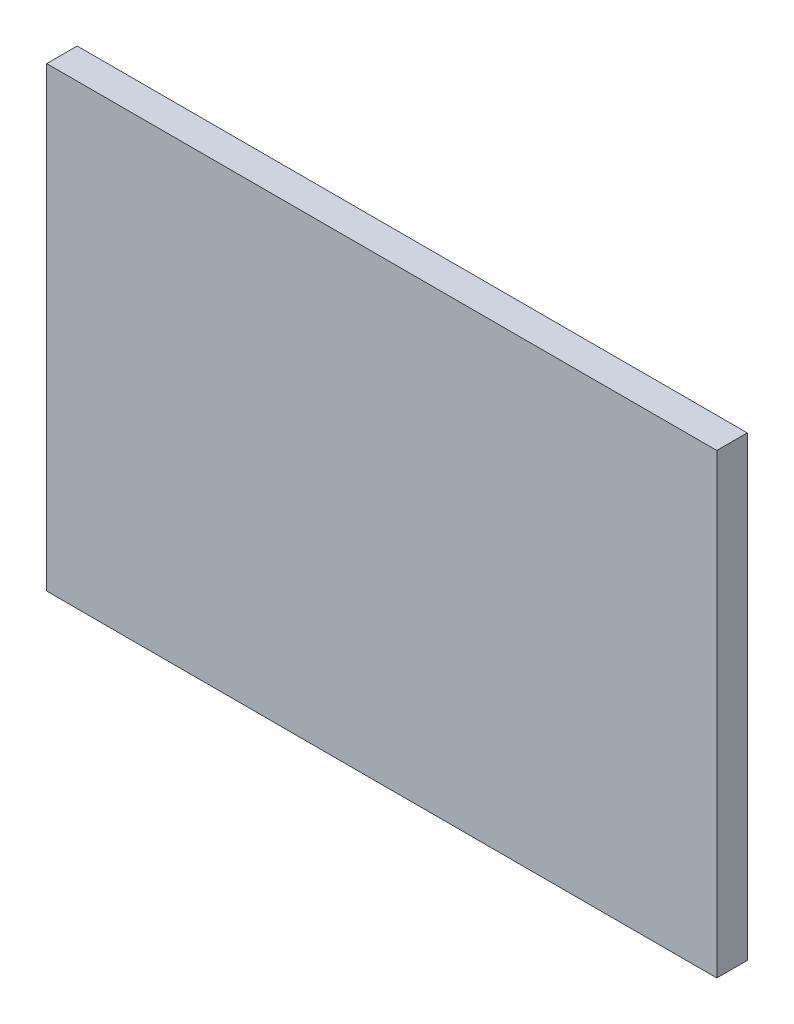
SolidWorks part; units mm, degrees
ref_plane "Alzado" through (0, 0, 0) normal (0, 0, 1) x (1, 0, 0)
ref_plane "Planta" through (0, 0, 0) normal (0, 1, 0) x (1, 0, 0)
ref_plane "Vista lateral" through (0, 0, 0) normal (1, 0, 0) x (0, 0, -1)
sketch "Croquis1" plane through (37728.547, 1888.5544, 0) normal (0, 0, 1) x (1, 0, 0)
  line L1 (-22281.5534, 13980.5825) -> (-281.5534, 13980.5825)
  line L2 (-22281.5534, 13980.5825) -> (-22281.5534, -1019.4175)
  line L3 (-22281.5534, -1019.4175) -> (-281.5534, -1019.4175)
  line L4 (-281.5534, 13980.5825) -> (-281.5534, -1019.4175)
  line L5 (-213.4399, 10638.8623) -> (6786.5601, 10638.8623)
  line L6 (-213.4399, 10638.8623) -> (-213.4399, 3638.8623)
  line L7 (-213.4399, 3638.8623) -> (6786.5601, 3638.8623)
  line L8 (6786.5601, 10638.8623) -> (6786.5601, 3638.8623)
  point P8 (0, 0)
  dimension "D1" = 15000
  dimension "D2" = 22000
  dimension "D3" = 7000
  dimension "D4" = 7000
extrude "Saliente-Extruir2" add sketch "Croquis1" along normal blind 1000 contours L1 L4 L3 L2
